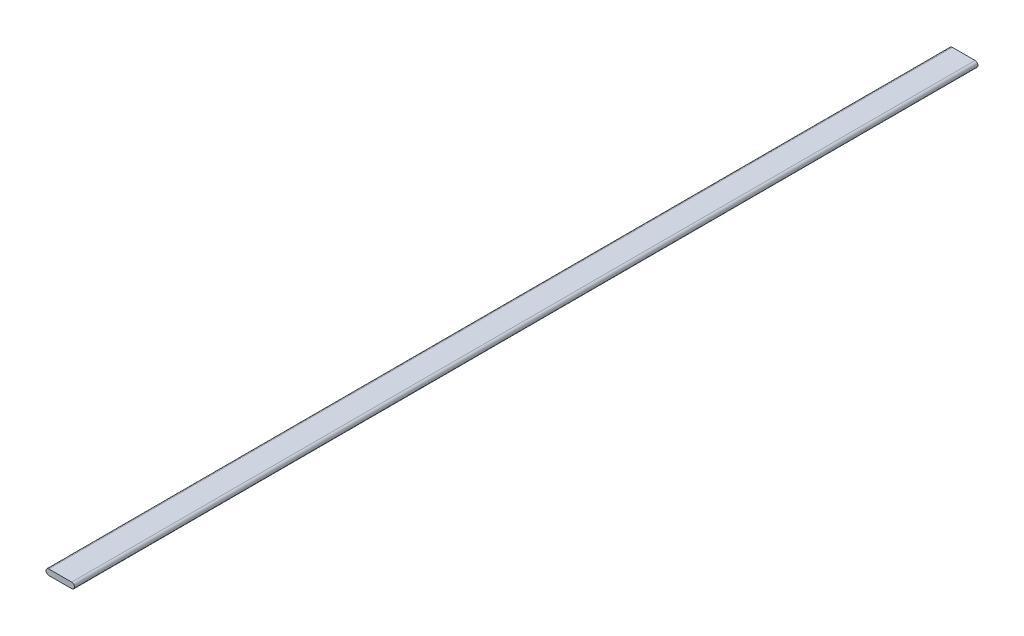
SolidWorks part; units mm, degrees
ref_plane "Front" through (0, 0, 0) normal (0, 0, 1) x (1, 0, 0)
ref_plane "Top" through (0, 0, 0) normal (0, 1, 0) x (1, 0, 0)
ref_plane "Right" through (0, 0, 0) normal (1, 0, 0) x (0, 0, -1)
sketch "Sketch2" plane through (0, 0, 0) normal (0, 0, 1) x (1, 0, 0)
  line L0 (9.8652, 0) -> (-9.8652, 0) construction
  line L1 (0, 0) -> (0, 5.4997) construction
  line L3 (-1.016, -0.254) -> (1.016, -0.254)
  line L4 (-1.016, 0.254) -> (1.016, 0.254)
  arc A1 (1.016, -0.254) -> (1.016, 0.254) centre (1.016, 0) ccw
  arc A3 (-1.016, 0.254) -> (-1.016, -0.254) centre (-1.016, 0) ccw
  dimension "D1" = 1.016
  dimension "D2" = 0.508
  dimension "D3" = 1.016
extrude "Boss-Extrude1" add sketch "Sketch2" along normal blind 40.259 and the other way blind 40.259
ref_plane "Plane1" through (0, 0, 27.559) normal (0, 0, 1) x (1, 0, 0)
ref_plane "Plane2" through (0, 0, -7.239) normal (0, 0, 1) x (1, 0, 0)
ref_plane "Plane3" [suppressed] through (0, 0, -40.259) normal (0, 0, -1) x (-1, 0, 0)
sketch "Sketch5" plane through (0, 0, 0) normal (1, 0, 0) x (0, 0, -1)
  line L4 (13.4124, 0) -> (40.259, 0)
  line L5 (40.259, -2.2817) -> (40.259, 2.2817) construction
  line L6 (4.3468, 26.0913) -> (15.3407, 37.9277)
  spline S2 degree 3 poles (-0.2595, 8.89) (-0.2595, 8.7854) (-0.2562, 8.576) (-0.2352, 8.1496) (-0.1784, 7.5979) (-0.0537, 6.9281) (0.1385, 6.2458) (0.4038, 5.5683) (0.7484, 4.9059) (1.1627, 4.2842) (1.7732, 3.5473) (2.4582, 2.9242) (3.1748, 2.4101) (3.5736, 2.1618) (3.8373, 2.0106) (4.0087, 1.9155) (4.3056, 1.7584) (4.8915, 1.476) (5.7296, 1.1387) (6.7318, 0.8182) (7.7183, 0.5679) (8.6917, 0.374) (9.9644, 0.1799) (11.2281, 0.0631) (12.4815, 0.0086) (13.1022, 0) (13.4124, 0) knots 0 0 0 0 0.017211 0.034421 0.070271 0.108552 0.14683 0.187421 0.228931 0.270473 0.311114 0.38734 0.422714 0.456353 0.464515 0.472594 0.488523 0.519567 0.579047 0.635899 0.690894 0.744496 0.797023 0.899663 0.949831 1 1 1 1
  spline S3 degree 3 poles (4.3468, 26.0913) (3.9578, 25.624) (3.5839, 25.0945) (2.8819, 23.8893) (2.5535, 23.215) (1.9508, 21.7551) (1.6766, 20.9695) (1.1864, 19.3319) (0.9703, 18.4803) (0.4075, 15.9045) (0.1468, 14.1571) (-0.1029, 11.8322) (-0.1628, 11.1056) (-0.2215, 10.1509) (-0.2359, 9.8562) (-0.2501, 9.4568) (-0.2537, 9.3297) (-0.2584, 9.0961) (-0.2595, 8.9956) (-0.2595, 8.89) knots 0 0 0 0 0.125 0.125 0.25 0.25 0.375 0.375 0.5 0.5 0.75 0.75 0.875 0.875 0.9375 0.9375 0.96875 0.96875 1 1 1 1
sketch "Sketch8" [suppressed] plane through (0, 0, -40.259) normal (0, 0, -1) x (-1, 0, 0)
  line L2 (1.016, 0.254) -> (-1.016, 0.254)
  line L3 (-1.016, -0.254) -> (1.016, -0.254)
  line L4 (1.016, 0.254) -> (-1.016, 0.254)
  line L5 (-1.016, -0.254) -> (1.016, -0.254)
  arc A3 (1.016, -0.254) -> (1.016, 0.254) centre (1.016, 0) ccw
  arc A4 (-1.016, 0.254) -> (-1.016, -0.254) centre (-1.016, 0) ccw
  arc A7 (1.016, -0.254) -> (1.016, 0.254) centre (1.016, 0) ccw
  arc A11 (-1.016, 0.254) -> (-1.016, -0.254) centre (-1.016, 0) ccw
  dimension "D1" = 0
sweep "Sweep2" [suppressed] add profiles "Sketch8" path "Sketch5"
delete or keep bodies "Body-Delete/Keep 1" [suppressed] type delete bodies bodies 104
